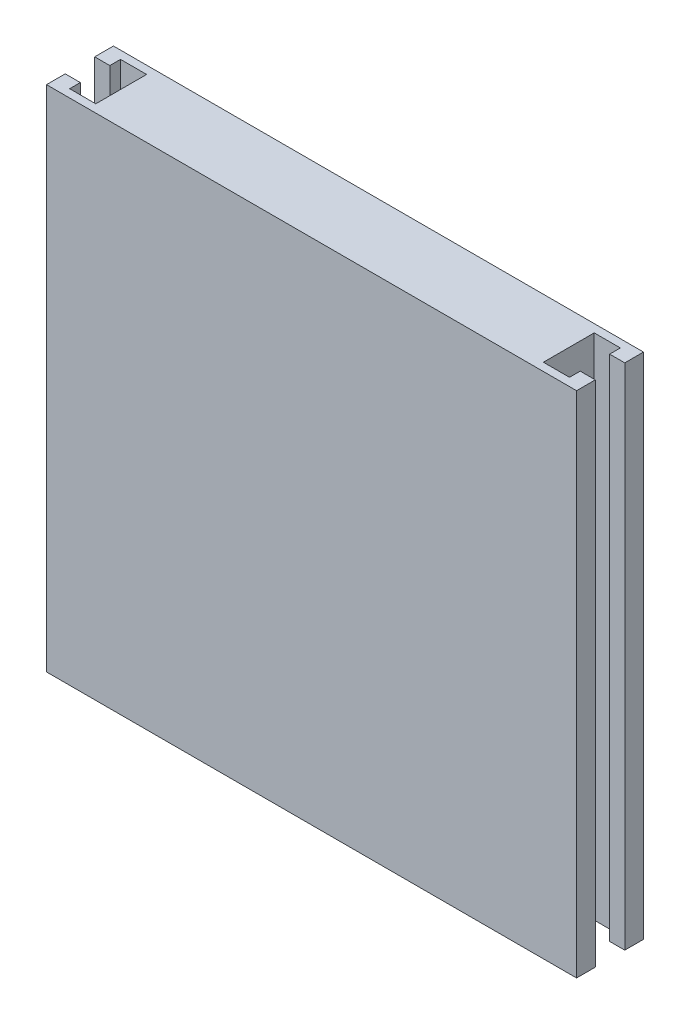
SolidWorks part; units mm, degrees
ref_plane "Piano frontale" through (0, 0, 0) normal (0, 0, 1) x (1, 0, 0)
ref_plane "Piano superiore" through (0, 0, 0) normal (0, 1, 0) x (1, 0, 0)
ref_plane "Piano destro" through (0, 0, 0) normal (1, 0, 0) x (0, 0, -1)
sketch "Schizzo2" plane through (0, 0, 0) normal (0, 1, 0) x (1, 0, 0)
  line L29 (331.8957, 607.8653) -> (315.9482, 607.8653)
  line L31 (316.5478, 607.8653) -> (316.5478, 600.8653)
  line L32 (316.5478, 600.8653) -> (322.1881, 600.8653)
  line L33 (322.1881, 604.8653) -> (322.1881, 600.8653)
  line L34 (322.1881, 607.8653) -> (415.5478, 607.8653)
  line L35 (415.5478, 607.8653) -> (415.5478, 582.8653)
  line L36 (415.5478, 582.8653) -> (316.5478, 582.8653)
  line L37 (316.5478, 582.8653) -> (316.5478, 589.8653)
  line L38 (316.5478, 589.8653) -> (322.1881, 589.8653)
  line L39 (322.1881, 589.8653) -> (322.1881, 585.8653)
  line L40 (322.1881, 585.8653) -> (331.9482, 585.8653)
  line L41 (331.9482, 585.8653) -> (331.9482, 604.8653)
  line L42 (331.9482, 604.8653) -> (322.1881, 604.8653)
  line L43 (316.5478, 607.8653) -> (322.1881, 607.8653)
  point P45 (327.0681, 604.8653)
  point P48 (327.0681, 585.8653)
  dimension "D14" = 9.7601
  dimension "D16" = 19
  dimension "D17" = 4
  dimension "D18" = 4
  dimension "D19" = 7
  dimension "D20" = 25
  dimension "D21" = 7
  dimension "D27" = 7
  dimension "D33" = 99
extrude "Estrusione-Estrusione1" add sketch "Schizzo2" along normal blind 190 contours L42 L41 L40 L39 L38 L37 L36 L35 L34 L29 L31 L32 L33
mirror "Specchia1" about plane through (415.5478, 190, 0) normal (1, 0, 0) of "Estrusione-Estrusione1"
